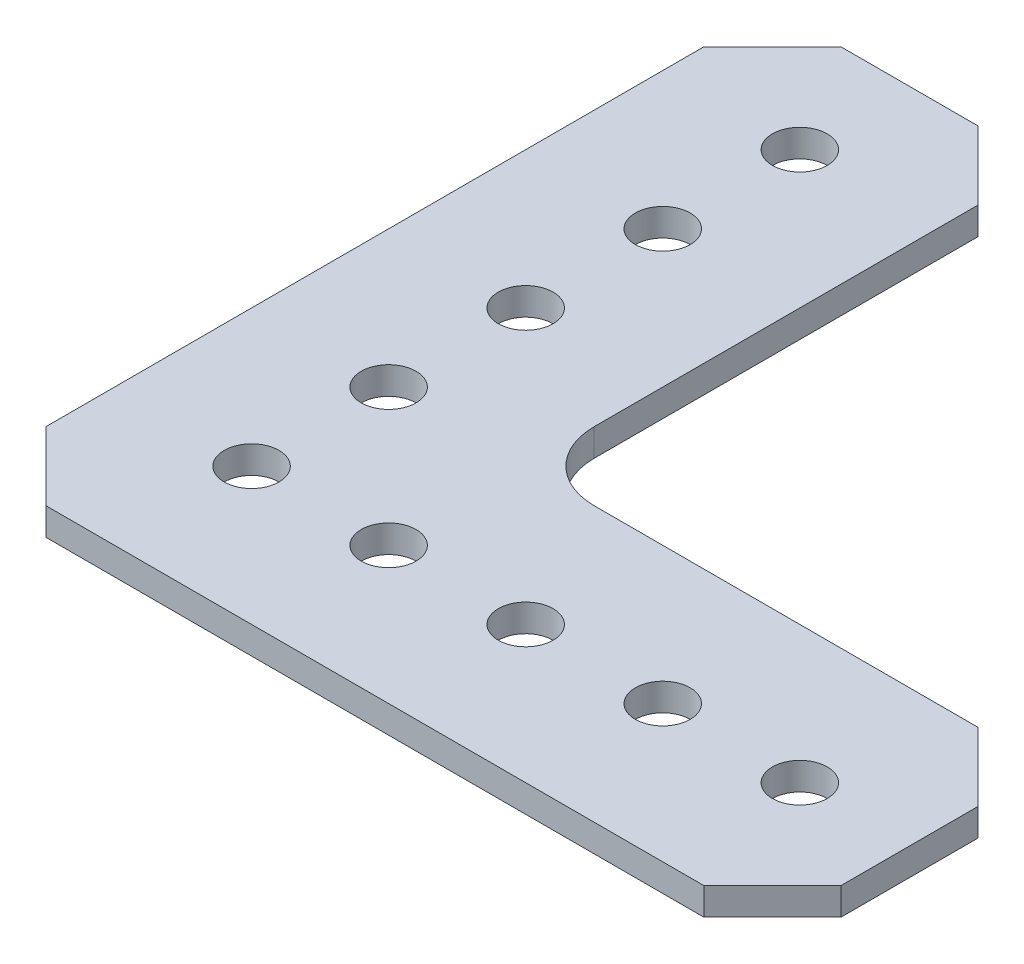
SolidWorks part; units mm, degrees
material "1060 合金"
ref_plane "前基準面" through (0, 0, 0) normal (0, 0, 1) x (1, 0, 0)
ref_plane "上基準面" through (0, 0, 0) normal (0, 1, 0) x (1, 0, 0)
ref_plane "右基準面" through (0, 0, 0) normal (1, 0, 0) x (0, 0, -1)
sketch "草圖1" plane through (0, 0, 0) normal (0, 1, 0) x (1, 0, 0)
  line L0 (0, 0) -> (0, -8) construction
  line L1 (0, -8) -> (0, -28) construction
  line L2 (0, -28) -> (0, -48) construction
  line L3 (0, -48) -> (20, -48) construction
  line L4 (20, -48) -> (40, -48) construction
  line L5 (40, -48) -> (48, -48) construction
  line L6 (-10, 0) -> (10, 0)
  line L7 (48, -38) -> (48, -58)
  line L8 (-10, 0) -> (-10, -58)
  line L9 (-10, -58) -> (48, -58)
  line L10 (10, 0) -> (10, -38)
  line L11 (10, -38) -> (48, -38)
  point P12 (0, 0)
  point P14 (48, -48)
  dimension "D1" = 8
  dimension "D2" = 20
  dimension "D3" = 20
extrude "填料-伸長1" add sketch "草圖1" along normal blind 2
hole_wizard "Ø4.0 (4) 直徑孔1" positions "草圖2" profile "草圖3" hole size "Ø4.0" standard "ISO" end condition through all
sketch "草圖2" plane through (0, 0, 0) normal (0, -1, 0) x (-1, 0, 0)
  point P0 (0, -28)
  point P3 (0, -48)
  point P6 (-20, -48)
  point P9 (-40, -48)
  point P13 (0, -8)
sketch "草圖3" plane through (0, 0, 28) normal (1, 0, 0) x (0, 0, -1)
  line L0 (0, 0) -> (0, 2)
  line L1 (0, 2) -> (2, 2)
  line L2 (2, 2) -> (2, 0)
  line L5 (2, 0) -> (0, 0)
  line L11 (0, -6.35) -> (0, 107.95) construction
  dimension "貫穿孔直徑" = 4
  dimension "貫穿孔深度" = 2
hole_wizard "Ø4.0 (4) 直徑孔2" positions "草圖4" profile "草圖5" hole size "Ø4.0" standard "ISO" end condition through all
sketch "草圖4" plane through (0, 0, 0) normal (0, -1, 0) x (-1, 0, 0)
  line L0 (-20, -48) -> (-40, -48) construction
  line L1 (0, -48) -> (-20, -48) construction
  line L2 (0, -28) -> (0, -48) construction
  line L3 (0, -8) -> (0, -28) construction
  point P0 (0, -18)
  point P2 (-10, -48)
  point P4 (0, -38)
  point P6 (-30, -48)
sketch "草圖5" plane through (0, 0, 18) normal (1, 0, 0) x (0, 0, -1)
  line L0 (0, 0) -> (0, 2)
  line L1 (0, 2) -> (2, 2)
  line L2 (2, 2) -> (2, 0)
  line L5 (2, 0) -> (0, 0)
  line L11 (0, -6.35) -> (0, 107.95) construction
  dimension "貫穿孔直徑" = 4
  dimension "貫穿孔深度" = 2
fillet "圓角1" radius 5 1 edges at (10, 1, 38)
chamfer "導角4" distance 5 angle 45 5 edges at (48, 1, 38) (48, 1, 58) (-10, 1, 58) (-10, 1, 0) (10, 1, 0)
